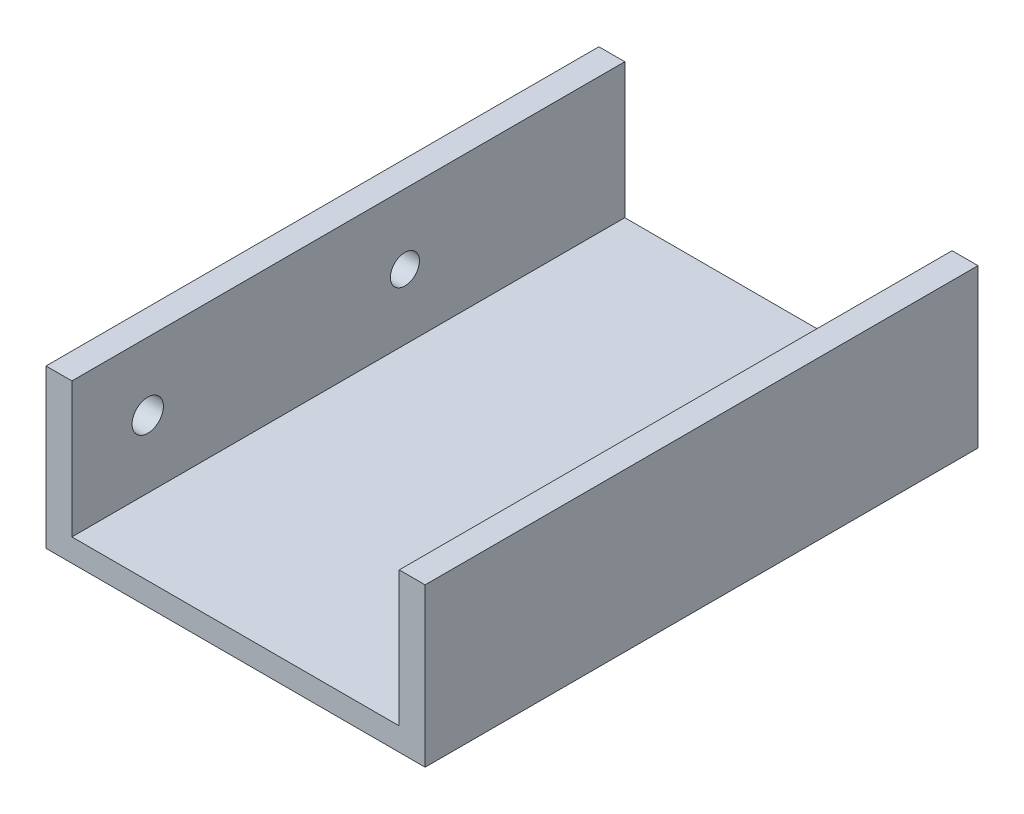
SolidWorks part; units mm, degrees
ref_plane "Front Plane" through (0, 0, 0) normal (0, 0, 1) x (1, 0, 0)
ref_plane "Top Plane" through (0, 0, 0) normal (0, 1, 0) x (1, 0, 0)
ref_plane "Right Plane" through (0, 0, 0) normal (1, 0, 0) x (0, 0, -1)
sketch "Sketch2" plane through (0, 0, 0) normal (0, 0, 1) x (1, 0, 0)
  line L0 (-38.1, 0) -> (38.1, 0)
  line L1 (-38.1, 0) -> (-38.1, 31.75)
  line L2 (-38.1, 31.75) -> (-32.893, 31.75)
  line L3 (-32.893, 31.75) -> (-32.893, 4.5974)
  line L4 (-32.893, 4.5974) -> (32.893, 4.5974)
  line L5 (32.893, 4.5974) -> (32.893, 31.75)
  line L6 (32.893, 31.75) -> (38.1, 31.75)
  line L7 (38.1, 31.75) -> (38.1, 0)
  point P8 (0, 4.5974)
  point P10 (0, 0)
  point P11 (35.4965, 31.75)
  dimension "D1" = 5.207
  dimension "D2" = 31.75
  dimension "D3" = 76.2
  dimension "D4" = 31.75
extrude "Boss-Extrude3" add sketch "Sketch2" along normal blind 111.125
sketch "Sketch4" plane through (-32.893, 0, 0) normal (1, 0, 0) x (0, 0, -1)
  line L0 (0, 4.5974) -> (0, 31.75) construction
  circle A0 centre (-44.196, 17.7352) radius 2.921
  dimension "D1" = 44.196
  dimension "D2" = 5.842
extrude "Cut-Extrude1" cut sketch "Sketch4" against normal through all
sketch "Sketch5" plane through (-32.893, 0, 0) normal (1, 0, 0) x (0, 0, -1)
  line L1 (-111.125, 4.5974) -> (-111.125, 31.75) construction
  circle A0 centre (-95.885, 18.1634) radius 3.1455
  dimension "D1" = 15.24
extrude "Cut-Extrude2" cut sketch "Sketch5" against normal through all
